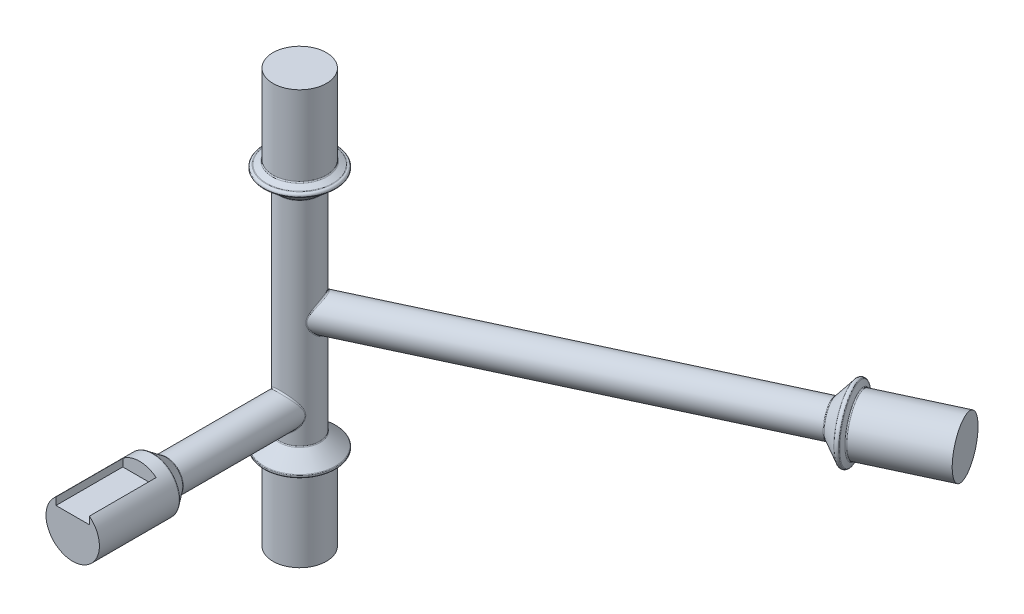
SolidWorks part; units mm, degrees
ref_plane "Front Plane" through (0, 0, 0) normal (0, 0, 1) x (1, 0, 0)
ref_plane "Top Plane" through (0, 0, 0) normal (0, 1, 0) x (1, 0, 0)
ref_plane "Right Plane" through (0, 0, 0) normal (1, 0, 0) x (0, 0, -1)
sketch "Sketch3" plane through (0, 0, 0) normal (0, 0, 1) x (1, 0, 0)
  line L1 (0, 31) -> (4, 31)
  line L2 (4, 31) -> (4, 19)
  line L3 (4, 19) -> (5, 18.5)
  line L9 (0, 31) -> (0, -31) construction
  line L10 (5.3653, 18) -> (3, 16)
  line L11 (3, 16) -> (3, 0)
  line L12 (3, 0) -> (0, 0)
  line L13 (3, -16) -> (3, 0)
  line L14 (5.3653, -18) -> (3, -16)
  line L15 (4, -19) -> (5, -18.5)
  line L16 (4, -31) -> (4, -19)
  line L17 (0, -31) -> (4, -31)
  arc A0 (5, 18.5) -> (5.3653, 18) centre (5.0548, 18.1566) cw
  arc A1 (5, -18.5) -> (5.3653, -18) centre (5.0548, -18.1566) ccw
  point P5 (4, 25)
  point P18 (4, -25)
  dimension "D1" = 4
  dimension "D2" = 25
  dimension "D3" = 12
  dimension "D4" = 0.5
  dimension "D5" = 16
  dimension "D6" = 2
  dimension "D7" = 2.3653
  dimension "D8" = 3
revolve "Revolve3" add sketch "Sketch3" angle 360 about L9
sketch "Sketch5" plane through (0, 0, 0) normal (0, 0, 1) x (1, 0, 0)
  line L7 (0, -9.5) -> (0, -14.5) construction
  circle A0 centre (0, -12) radius 2.5
extrude "Boss-Extrude3" add sketch "Sketch5" along normal blind 20
sketch "Sketch7" plane through (0, 0, 20) normal (0, 0, 1) x (1, 0, 0)
  circle A0 centre (0, -12) radius 4
  dimension "D1" = 8
extrude "Boss-Extrude4" add sketch "Sketch7" along normal blind 14
sketch "Sketch8" plane through (0, 0, 0) normal (1, 0, 0) x (0, 0, -1)
  line L0 (-20, -9.5) -> (-22, -8)
  line L1 (-20, -8) -> (-34, -8) construction
  line L2 (-22, -8) -> (-20, -8)
  line L3 (-20, -16) -> (-20, -8) construction
  line L4 (-20, -8) -> (-20, -9.5)
  line L5 (-34, -12) -> (-20, -12) construction
  dimension "D1" = 2
revolve "Cut-Revolve1" cut sketch "Sketch8" angle 360 about L5
ref_plane "Plane1" through (0, -8, 0) normal (0, 1, 0) x (1, 0, 0)
sketch "Sketch9" plane through (0, -8, 0) normal (0, 1, 0) x (1, 0, 0)
  line L0 (0, -200034) -> (0, 199980) construction
  line L1 (2.5, -24) -> (-2.5, -24)
  line L2 (2.5, -24) -> (2.5, -34)
  line L3 (2.5, -34) -> (-2.5, -34)
  line L4 (-2.5, -24) -> (-2.5, -34)
  line L5 (2.5, -24) -> (-2.5, -34) construction
  line L6 (2.5, -34) -> (-2.5, -24) construction
  line L7 (-4, -34) -> (4, -34) construction
  point P0 (0, -29)
  dimension "D1" = 5
  dimension "D2" = 10
extrude "Cut-Extrude1" cut sketch "Sketch9" against normal blind 2
sketch "Sketch10" plane through (0, 0, 0) normal (0, 1, 0) x (1, 0, 0)
  line L0 (0, 0) -> (54.3785, 25.3571)
  line L1 (0, -200034) -> (0, 199980) construction
  line L3 (55.435, 23.0913) -> (1.0565, -2.2658)
  line L4 (1.0565, -2.2658) -> (0, 0)
  line L5 (55.435, 23.0913) -> (58.165, 21.831)
  line L6 (58.7879, 22.9997) -> (58.8406, 22.0011)
  line L8 (58.7879, 22.9997) -> (69.6636, 28.0711)
  line L9 (69.6636, 28.0711) -> (67.9731, 31.6964)
  line L10 (67.9731, 31.6964) -> (54.3785, 25.3571)
  arc A0 (58.165, 21.831) -> (58.8406, 22.0011) centre (58.4369, 22.1778) ccw
  dimension "D1" = 115
  dimension "D2" = 2.5
  dimension "D3" = 60
  dimension "D4" = 15
  dimension "D5" = 4
  dimension "D6" = 12
  dimension "D7" = 1
  dimension "D8" = 2.73
  dimension "D9" = 130.22
revolve "Revolve4" add sketch "Sketch10" angle 360 about L0
fillet "Fillet1" radius 0.2 15 edges at (-5, -18.5, 0) (58.7879, 0, -22.9997) (58.8406, 0, -22.0011) (58.165, 0, -21.831) (55.435, 0, -23.0913) (-5.3653, -18, 0) (-3, -16, 0) (4, -12, 22) (2.5, -12, 20) (2.4698, -12.3876, 1.703) (0.4997, 0.3876, -2.9581) (-4, 19, 0) (-5, 18.5, 0) (-5.3653, 18, 0) (-3, 16, 0)
